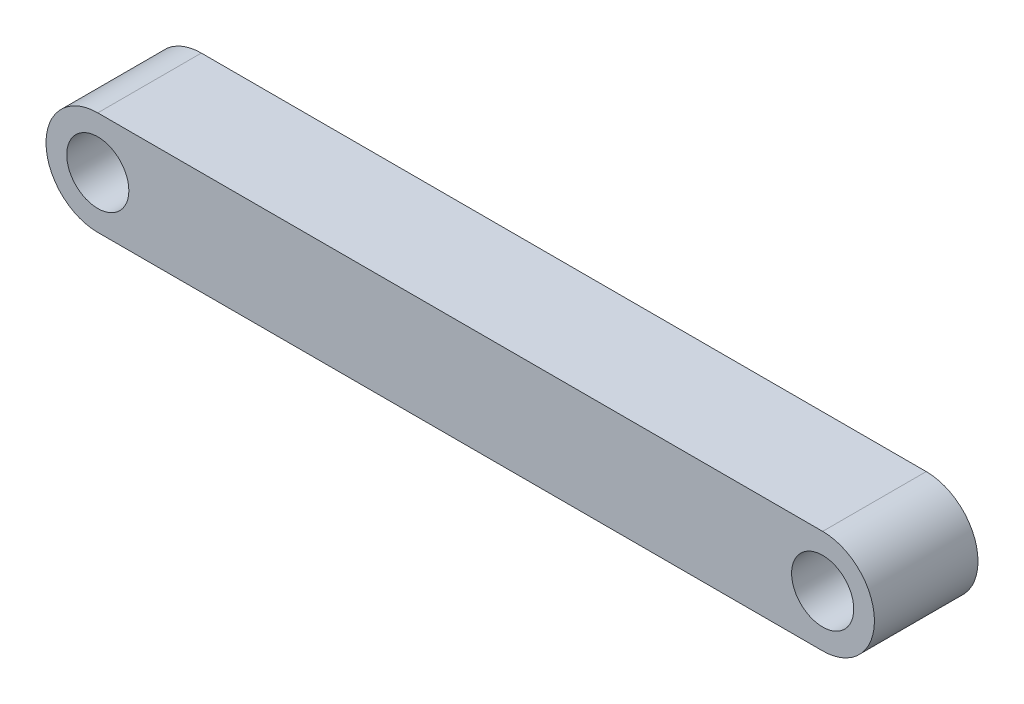
SolidWorks part; units mm, degrees
ref_plane "Front Plane" through (0, 0, 0) normal (0, 0, 1) x (1, 0, 0)
ref_plane "Top Plane" through (0, 0, 0) normal (0, 1, 0) x (1, 0, 0)
ref_plane "Right Plane" through (0, 0, 0) normal (1, 0, 0) x (0, 0, -1)
sketch "Sketch1" plane through (0, 0, 0) normal (0, 0, 1) x (1, 0, 0)
  line L1 (70, -10) -> (-70, -10)
  line L3 (70, 10) -> (-70, 10)
  line L5 (70, -10) -> (-70, 10) construction
  line L6 (70, 10) -> (-70, -10) construction
  arc A0 (-70, 10) -> (-70, -10) centre (-70, 0) ccw
  arc A1 (70, 10) -> (70, -10) centre (70, 0) cw
  point P0 (0, 0)
  point P7 (-80, 0)
  point P9 (80, 0)
  dimension "D3" = 160
  dimension "D1" = 140
  dimension "D2" = 20
extrude "Boss-Extrude1" add sketch "Sketch1" along normal blind 20
sketch "Sketch2" plane through (0, 0, 20) normal (0, 0, 1) x (1, 0, 0)
  circle A0 centre (-70, 0) radius 6
  circle A1 centre (70, 0) radius 6
  dimension "D1" = 12
extrude "Cut-Extrude1" cut sketch "Sketch2" against normal through all
